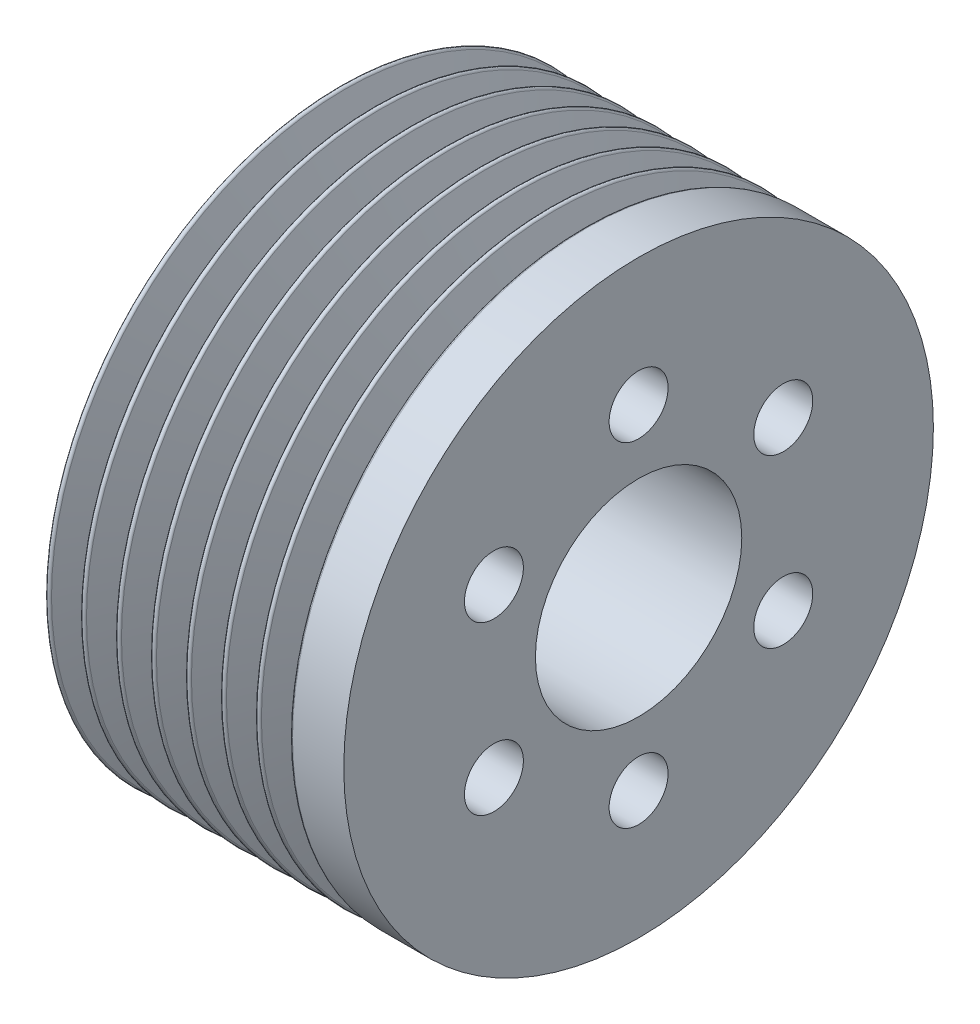
SolidWorks part; units mm, degrees
material "2018 Alloy"
ref_plane "Front Plane" through (0, 0, 0) normal (0, 0, 1) x (1, 0, 0)
ref_plane "Top Plane" through (0, 0, 0) normal (0, 1, 0) x (1, 0, 0)
ref_plane "Right Plane" through (0, 0, 0) normal (1, 0, 0) x (0, 0, -1)
sketch "Sketch1" plane through (0, 0, 0) normal (0, 0, 1) x (1, 0, 0)
  line L0 (49, 10.5) -> (49, 0) construction
  line L1 (49, 10.5) -> (49, 30)
  line L2 (49, 30) -> (18, 30)
  line L3 (18, 30) -> (18, 21.5)
  line L4 (49, 10.5) -> (31.5, 10.5)
  line L5 (0, 0) -> (49, 0) construction
  line L6 (18, 21.5) -> (31.5, 21.5)
  line L8 (0, 8.3175) -> (0, 0) construction
  line L9 (31.5, 10.5) -> (31.5, 21.5)
  dimension "D1" = 31
  dimension "D2" = 60
  dimension "D3" = 31.5
  dimension "D4" = 43
  dimension "D5" = 49
  dimension "D8" = 21
revolve "Revolve1" add sketch "Sketch1" angle 360 about L5
sketch "Sketch2" plane through (0, 0, 0) normal (0, 0, 1) x (1, 0, 0)
  line L0 (43.5458, 29.8376) -> (42.281, 26.4546)
  line L1 (41.719, 26.4546) -> (40.4542, 29.8376)
  line L2 (43.5458, 29.8376) -> (43.6066, 30) construction
  line L3 (49, 30) -> (18, 30) construction
  line L4 (40.4542, 29.8376) -> (40.3934, 30) construction
  line L5 (49, -30) -> (49, 30) construction
  line L6 (43.78, 30) -> (40.22, 30)
  line L7 (0, 0) -> (49, 0) construction
  arc A0 (43.5458, 29.8376) -> (43.78, 30) centre (43.78, 29.75) cw
  arc A1 (40.4542, 29.8376) -> (40.22, 30) centre (40.22, 29.75) ccw
  arc A2 (42.281, 26.4546) -> (41.719, 26.4546) centre (42, 26.5597) cw
  dimension "D2" = 0.25
  dimension "D3" = 0.3
  dimension "D1" = 41
  dimension "D4" = 3.56
  dimension "D5" = 7
revolve "Cut-Revolve1" cut sketch "Sketch2" angle 360 about L7
pattern_linear "LPattern1" count 8 spacing 3.56 along (-1, 0, 0) of "Cut-Revolve1"
sketch "Sketch3" plane through (49, 0, 0) normal (1, 0, 0) x (0, 0, -1)
  circle A0 centre (0, 0) radius 17 construction
  circle A1 centre (0, 17) radius 3
  circle A2 centre (14.7224, 8.5) radius 3
  circle A3 centre (14.7224, -8.5) radius 3
  circle A4 centre (0, -17) radius 3
  circle A5 centre (-14.7224, -8.5) radius 3
  circle A6 centre (-14.7224, 8.5) radius 3
  dimension "D1" = 34
  dimension "D2" = 6
  dimension "D3" = 6
extrude "Cut-Extrude1" cut sketch "Sketch3" against normal up to surface (17.5 mm away) up to face at (31.5, 0, 10.5)
